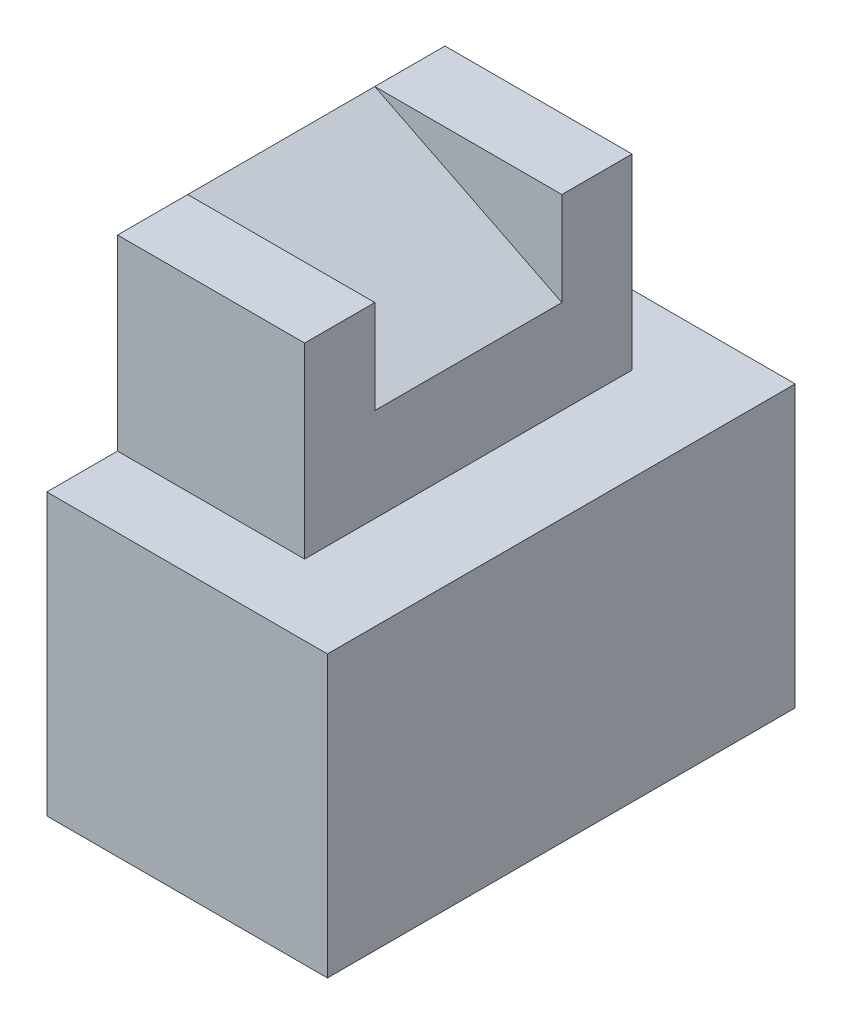
SolidWorks part; units mm, degrees
ref_plane "Alzado" through (0, 0, 0) normal (0, 0, 1) x (1, 0, 0)
ref_plane "Planta" through (0, 0, 0) normal (0, 1, 0) x (1, 0, 0)
ref_plane "Vista lateral" through (0, 0, 0) normal (1, 0, 0) x (0, 0, -1)
sketch "Croquis1" plane through (0, 0, 0) normal (0, 1, 0) x (1, 0, 0)
  line L1 (-3, 5) -> (3, 5)
  line L2 (-3, 5) -> (-3, -5)
  line L3 (-3, -5) -> (3, -5)
  line L4 (3, 5) -> (3, -5)
  line L5 (-3, 5) -> (3, -5) construction
  line L6 (-3, -5) -> (3, 5) construction
  point P0 (0, 0)
  dimension "D1" = 10
  dimension "D2" = 6
extrude "Saliente-Extruir1" add sketch "Croquis1" along normal blind 6
sketch "Croquis2" plane through (0, 6, 0) normal (0, 1, 0) x (1, 0, 0)
  line L1 (-3, 5) -> (-3, -5) construction
  line L9 (-3, 3.5124) -> (-3, 5)
  line L10 (-3, -3.4876) -> (1, -3.4876)
  line L11 (1, -3.4876) -> (1, 3.5124)
  line L14 (-3, -3.4876) -> (-3, 3.5124)
  line L15 (-3, 3.5124) -> (1, 3.5124)
  line M16 (-3, 5) -> (-3, -5)
extrude "Saliente-Extruir3" add sketch "Croquis2" along normal blind 4 contours L15 L10 L11 M16
sketch "Croquis4" plane through (0, 10, 0) normal (0, 1, 0) x (1, 0, 0)
  line L1 (-3, 3.5124) -> (-3, -3.4876) construction
  line L3 (-3, 2.0124) -> (-3, -1.9876)
  line L4 (-3, -1.9876) -> (1, -1.9876)
  line L5 (1, -3.4876) -> (1, 3.5124) construction
  line L6 (-3, 2.0124) -> (1, 2.0124)
  line L7 (1, -3.4876) -> (1, 3.5124) construction
  line L8 (1, 2.0124) -> (1, -1.9876)
  dimension "D3" = 4
extrude "Cortar-Extruir1" cut sketch "Croquis4" against normal blind 2
sketch "Croquis6" plane through (0, 0, -2.0124) normal (0, 0, 1) x (1, 0, 0)
  line L0 (-3, 10) -> (1, 8)
  line L1 (-3, 10) -> (-3, 8)
  line L2 (-3, 8) -> (1, 8)
extrude "Saliente-Extruir5" add sketch "Croquis6" along normal blind 4
